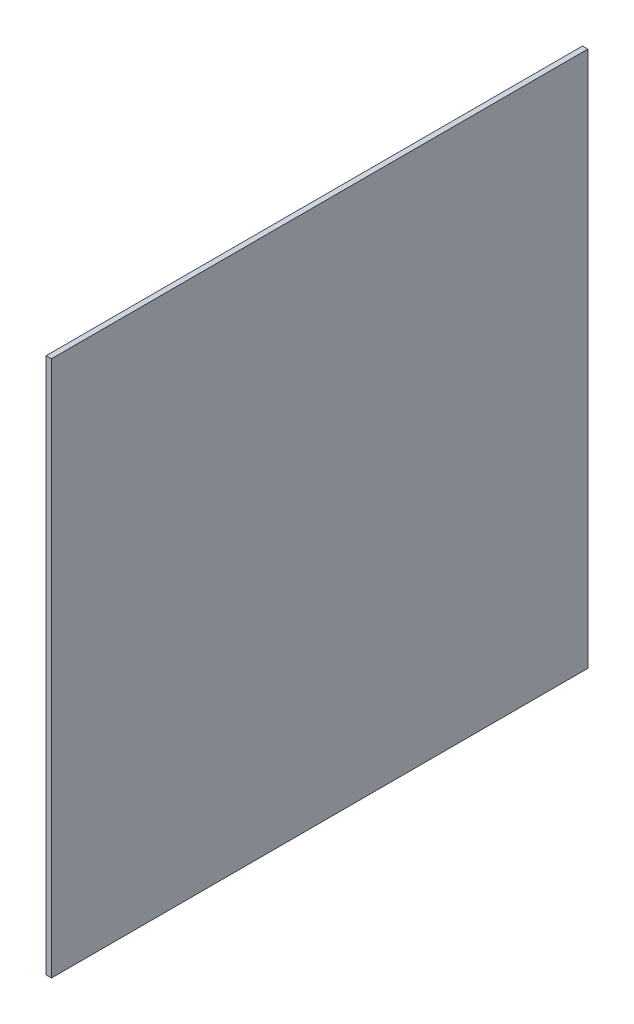
SolidWorks part; units mm, degrees
ref_plane "Front Plane" through (0, 0, 0) normal (0, 0, 1) x (1, 0, 0)
ref_plane "Top Plane" through (0, 0, 0) normal (0, 1, 0) x (1, 0, 0)
ref_plane "Right Plane" through (0, 0, 0) normal (1, 0, 0) x (0, 0, -1)
sketch "Sketch2" plane through (0, 0, 0) normal (1, 0, 0) x (0, 0, -1)
  line L1 (-150, 150) -> (150, 150)
  line L2 (-150, 150) -> (-150, -150)
  line L3 (-150, -150) -> (150, -150)
  line L4 (150, 150) -> (150, -150)
  line L5 (-150, 150) -> (150, -150) construction
  line L6 (-150, -150) -> (150, 150) construction
  point P0 (0, 0)
  dimension "D1" = 300
  dimension "D2" = 300
extrude "Boss-Extrude1" add sketch "Sketch2" along normal blind 3
